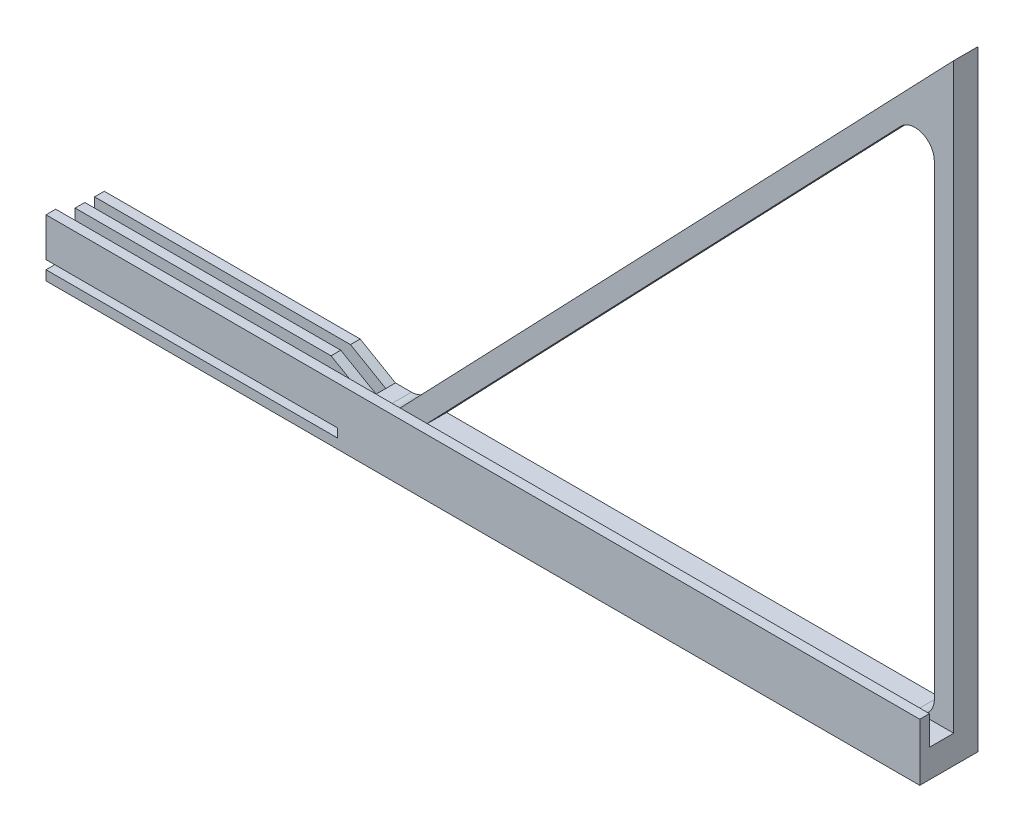
SolidWorks part; units mm, degrees
ref_plane "Front Plane" through (0, 0, 0) normal (0, 0, 1) x (1, 0, 0)
ref_plane "Top Plane" through (0, 0, 0) normal (0, 1, 0) x (1, 0, 0)
ref_plane "Right Plane" through (0, 0, 0) normal (1, 0, 0) x (0, 0, -1)
sketch "Sketch1" plane through (0, 0, 0) normal (0, 0, 1) x (1, 0, 0)
  line L0 (0, 0) -> (228.6, 0)
  line L1 (228.6, 0) -> (228.6, 7.366)
  line L2 (228.6, 7.366) -> (0, 7.366)
  line L3 (0, 7.366) -> (0, 4.826)
  line L4 (0, 4.826) -> (76.2, 4.826)
  line L5 (76.2, 4.826) -> (76.2, 2.54)
  line L6 (76.2, 2.54) -> (0, 2.54)
  line L7 (0, 2.54) -> (0, 0)
  dimension "D1" = 228.6
  dimension "D2" = 76.2
  dimension "D3" = 2.286
  dimension "D4" = 2.54
extrude "Boss-Extrude1" add sketch "Sketch1" along normal blind 15.24
sketch "Sketch2" plane through (0, 0, 0) normal (0, 0, 1) x (1, 0, 0)
  line L0 (228.6, 7.366) -> (228.6, 159.766)
  line L1 (228.6, 159.766) -> (82.55, 7.366)
  line L2 (228.6, 7.366) -> (0, 7.366) construction
  line L4 (76.2, 4.826) -> (76.2, 2.54) construction
  line L5 (223.52, 7.366) -> (223.52, 147.1231)
  line L6 (223.52, 147.1231) -> (89.5861, 7.366)
  line L7 (223.52, 147.1231) -> (86.2177, 3.8511) construction
  line L8 (82.55, 7.366) -> (89.5861, 7.366)
  line L9 (223.52, 7.366) -> (228.6, 7.366)
  dimension "D1" = 6.35
  dimension "D2" = 152.4
  dimension "D4" = 43.781
  dimension "D3" = 5.08
extrude "Boss-Extrude2" add sketch "Sketch2" along normal blind 6.35
sketch "Sketch3" plane through (0, 0, 0) normal (0, 0, 1) x (1, 0, 0)
  line L1 (0, 0) -> (76.2, 0)
  line L2 (0, 0) -> (0, 12.7)
  line L3 (0, 12.7) -> (76.2, 12.7)
  line L4 (76.2, 0) -> (76.2, 12.7)
  dimension "D1" = 12.7
extrude "Boss-Extrude3" add sketch "Sketch3" along normal blind 7.62
sketch "Sketch5" plane through (0, 0, 0) normal (-1, 0, 0) x (0, 0, 1)
  line L8 (7.62, 2.54) -> (2.54, 2.54)
  line L9 (2.54, 2.54) -> (2.54, 12.7)
  line L10 (7.62, 12.7) -> (0, 12.7) construction
  line L11 (2.54, 12.7) -> (5.08, 12.7)
  line L12 (5.08, 12.7) -> (5.08, 4.826)
  line L13 (5.08, 4.826) -> (7.62, 4.826)
  line L14 (7.62, 4.826) -> (7.62, 2.54)
  line L15 (0, 12.7) -> (0, 0) construction
  dimension "D1" = 2.54
  dimension "D2" = 2.54
extrude "Cut-Extrude1" cut sketch "Sketch5" against normal up to surface (76.2 mm away) up to face at (76.2, 3.683, 11.43)
sketch "Sketch7" plane through (0, 0, 7.62) normal (0, 0, 1) x (1, 0, 0)
  line L0 (76.2, 7.366) -> (66.9612, 12.7)
  line L1 (76.2, 12.7) -> (0, 12.7) construction
  line L2 (66.9612, 12.7) -> (76.2, 12.7)
  line L3 (76.2, 12.7) -> (76.2, 7.366)
  dimension "D1" = 60
extrude "Cut-Extrude2" cut sketch "Sketch7" against normal through all
fillet "Fillet1" radius 1.27 2 edges at (38.1, 2.54, 2.54) (38.1, 4.826, 5.08)
fillet "Fillet2" radius 5.08 3 edges at (223.52, 7.366, 3.175) (82.55, 7.366, 3.175) (223.52, 147.1231, 3.175)
sketch "Sketch6" plane through (0, 7.366, 0) normal (0, 1, 0) x (1, 0, 0)
  line L0 (228.6, -15.24) -> (228.6, -6.35) construction
  line L1 (0, -15.24) -> (228.6, -15.24)
  line L2 (0, -15.24) -> (0, -12.7)
  line L3 (0, -12.7) -> (228.6, -12.7)
  line L4 (228.6, -15.24) -> (228.6, -12.7)
  dimension "D1" = 2.54
extrude "Boss-Extrude4" add sketch "Sketch6" along normal blind 7.62
chamfer "Chamfer1" [suppressed] distance 5.334 angle 60
